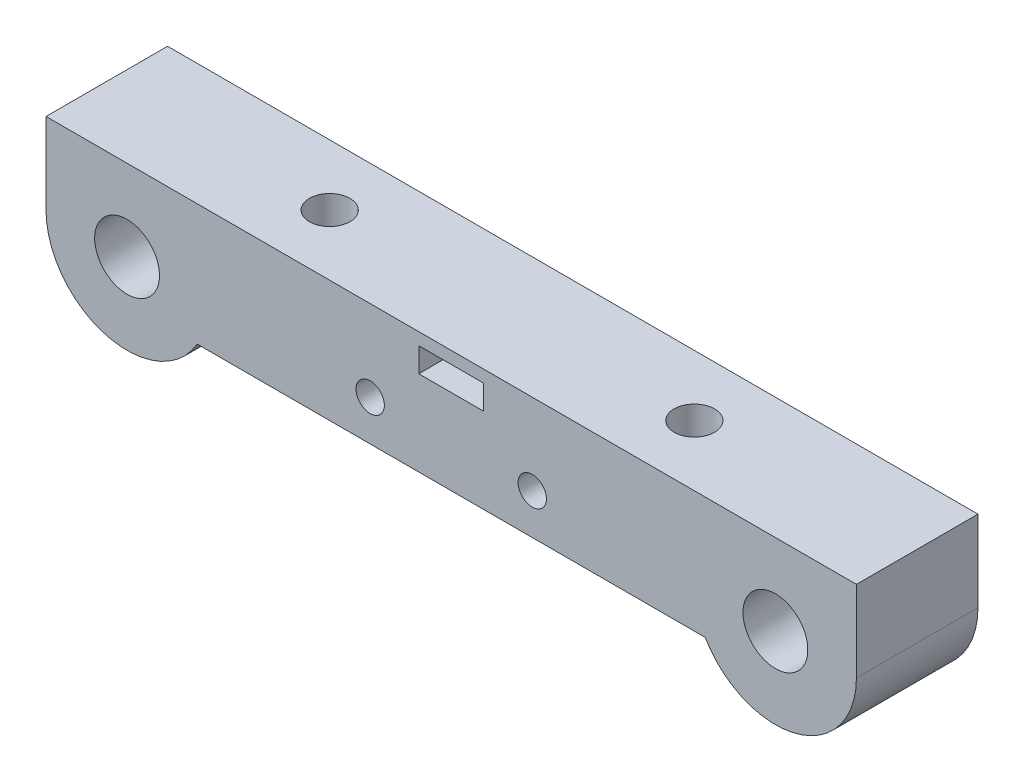
SolidWorks part; units mm, degrees
material "ABS"
ref_plane "Plano frontal" through (0, 0, 0) normal (0, 0, 1) x (1, 0, 0)
ref_plane "Plano superior" through (0, 0, 0) normal (0, 1, 0) x (1, 0, 0)
ref_plane "Plano direito" through (0, 0, 0) normal (1, 0, 0) x (0, 0, -1)
sketch "Esboço1" plane through (0, 0, 0) normal (0, 0, 1) x (1, 0, 0)
  line L0 (0, 0) -> (0, -15) construction
  line L1 (50, 0) -> (50, -10)
  line L2 (-50, -10) -> (-50, 0)
  line L3 (-50, 0) -> (50, 0)
  line L4 (10, -10) -> (-10, -10) construction
  line L5 (4, -1.5) -> (-4, -1.5)
  line L6 (4, -1.5) -> (4, -4.5)
  line L7 (-31.3397, -15) -> (31.3397, -15)
  line L8 (4, -4.5) -> (-4, -4.5)
  line L9 (-4, -1.5) -> (-4, -4.5)
  line L10 (4, -1.5) -> (-4, -4.5) construction
  line L11 (4, -4.5) -> (-4, -1.5) construction
  circle A0 centre (-40, -10) radius 4
  circle A1 centre (40, -10) radius 4
  arc A2 (-50, -10) -> (-31.3397, -15) centre (-40, -10) ccw
  arc A3 (50, -10) -> (31.3397, -15) centre (40, -10) cw
  circle A4 centre (10, -10) radius 1.75
  circle A5 centre (-10, -10) radius 1.75
  point P0 (0, 0)
  point P2 (0, -3)
  point P10 (40, -20)
  point P13 (63, -13)
  point P24 (0, -10)
  point P26 (0, 0)
  dimension "D3" = 8
  dimension "D4" = 80
  dimension "D2" = 10
  dimension "D8" = 3.5
  dimension "D1" = 100
  dimension "D5" = 3
  dimension "D6" = 8
  dimension "D7" = 3
  dimension "D9" = 20
  dimension "D10" = 15
  dimension "D11" = 5
extrude "Ressalto-extrusão1" add sketch "Esboço1" along normal blind 15
sketch "Esboço2" plane through (0, -15, 0) normal (0, -1, 0) x (1, 0, 0)
  line L0 (0, 0) -> (0, 15) construction
  line L1 (-31.3397, 0) -> (31.3397, 0) construction
  line L2 (-31.3397, 15) -> (31.3397, 15) construction
  circle A0 centre (-22.5, 7.5) radius 2.5
  circle A1 centre (22.5, 7.5) radius 2.5
  point P11 (0, 7.5)
  dimension "D2" = 5
  dimension "D1" = 45
extrude "Corte-extrusão1" cut sketch "Esboço2" against normal blind 15 contours A1 | A0
